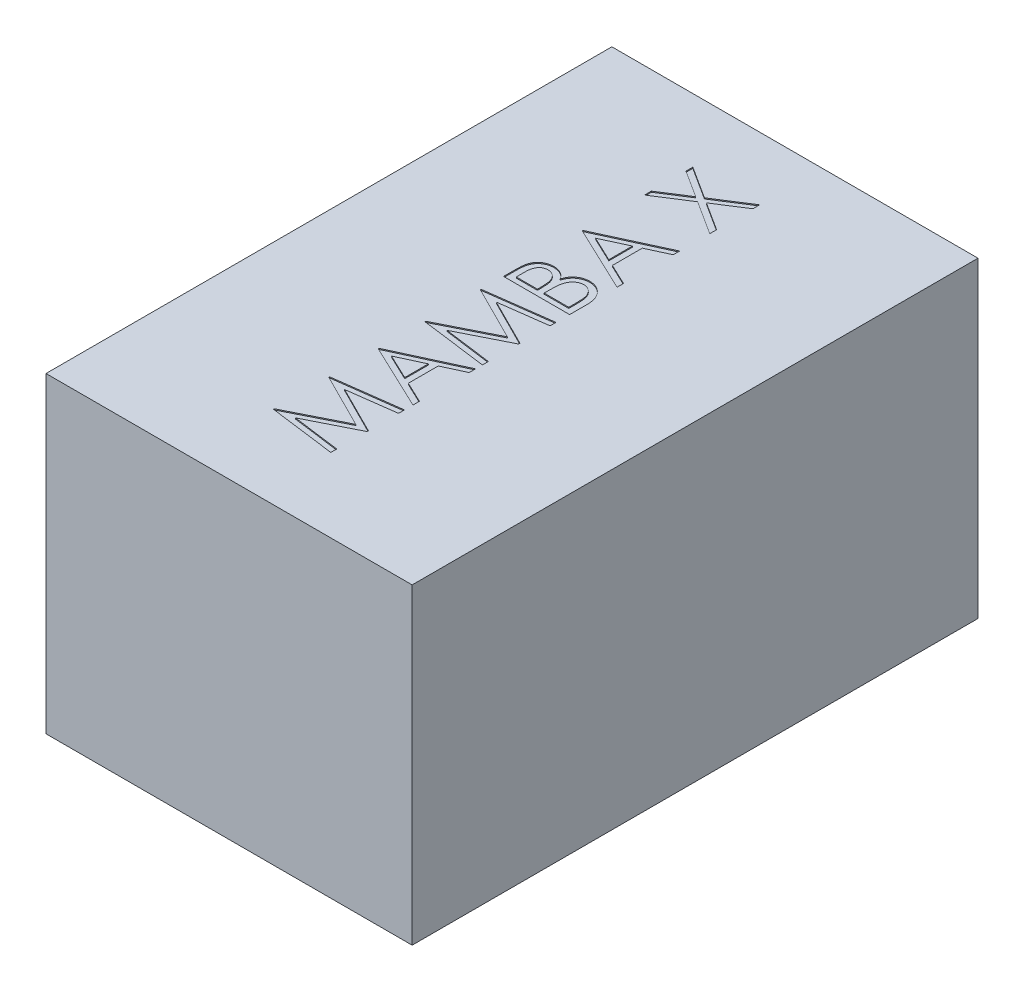
SolidWorks part; units mm, degrees
ref_plane "Front" through (0, 0, 0) normal (0, 0, 1) x (1, 0, 0)
ref_plane "Top" through (0, 0, 0) normal (0, 1, 0) x (1, 0, 0)
ref_plane "Right" through (0, 0, 0) normal (1, 0, 0) x (0, 0, -1)
sketch "Sketch1" plane through (0, 0, 0) normal (0, 1, 0) x (1, 0, 0)
  line L1 (17.6, -27.2) -> (-17.6, -27.2)
  line L2 (17.6, -27.2) -> (17.6, 27.2)
  line L3 (17.6, 27.2) -> (-17.6, 27.2)
  line L4 (-17.6, -27.2) -> (-17.6, 27.2)
  line L5 (17.6, -27.2) -> (-17.6, 27.2) construction
  line L6 (17.6, 27.2) -> (-17.6, -27.2) construction
  point P0 (0, 0)
  dimension "D1" = 54.4
  dimension "D2" = 35.2
extrude "Boss-Extrude1" add sketch "Sketch1" along normal blind 30
sketch "Sketch2" plane through (0, 30, 0) normal (0, 1, 0) x (1, 0, 0)
  line L0 (2.6637, -20.5718) -> (2.6637, 23.5766) construction
  text T0 "MAMBA X"
  point P3 (8.0022, -18.5785)
  point P4 (0, 0)
  point P5 (0, 0)
  point P6 (4.4303, -21.1047)
  point P7 (4.5678, -19.013)
  point P8 (2.6637, -20.5718)
extrude "Cut-Extrude1" cut sketch "Sketch2" against normal blind 0.1
